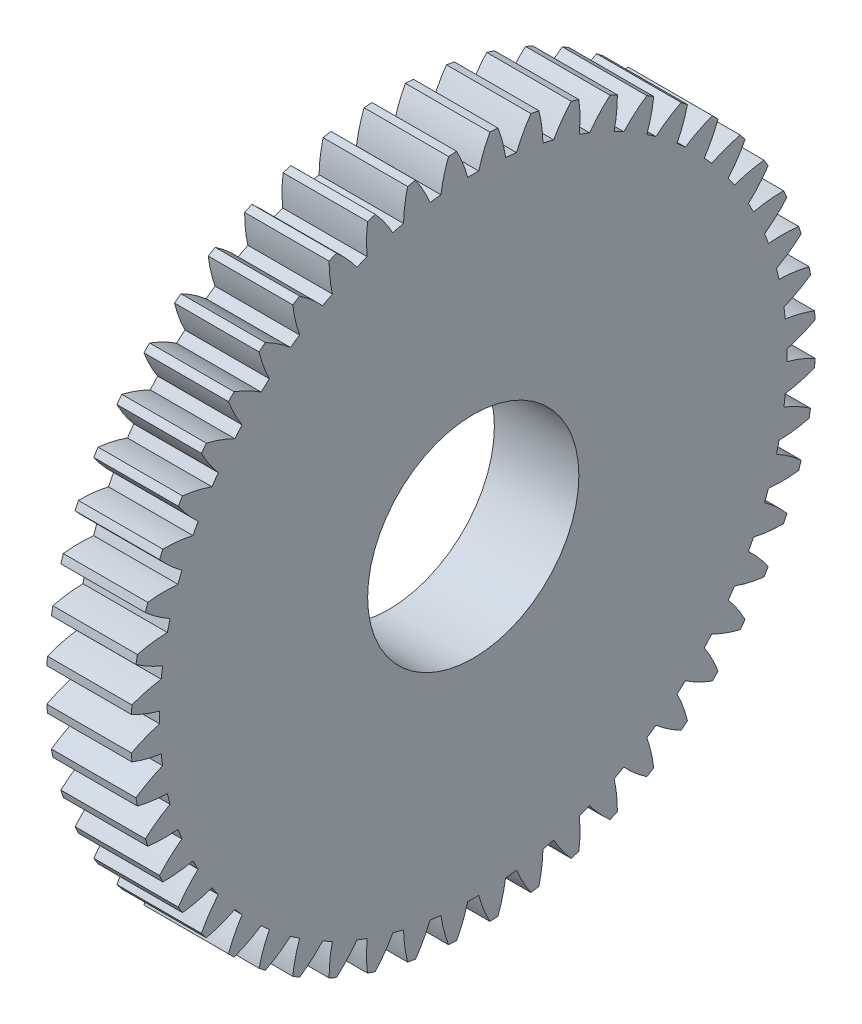
SolidWorks part; units mm, degrees
ref_plane "Plane1" through (0, 0, 0) normal (0, 0, 1) x (1, 0, 0)
ref_plane "Plane2" through (0, 0, 0) normal (0, 1, 0) x (1, 0, 0)
ref_plane "Plane3" through (0, 0, 0) normal (1, 0, 0) x (0, 0, -1)
sketch "HoldingSke" plane through (0, 0, 0) normal (0, 1, 0) x (1, 0, 0)
  line L0 (0, 0) -> (1.0261, -1.3134)
  line L1 (-15, 0) -> (100, 0) construction
  line L2 (0, 0) -> (-2.1039, 2.3779)
  line L3 (0, 0) -> (-11.863, 4.5341)
  line L4 (0, 0) -> (5.3169, 6.8053)
  line L5 (0, 0) -> (-46.8476, -17.4728)
  line L6 (0, 0) -> (-3.3159, -2.2372)
  line L7 (-2.1039, 2.3779) -> (8.6586, 51.2059)
  line L8 (-76.2, 54.61) -> (-74.4, 54.61)
  line L9 (-71.009, 38.7566) -> (-53.1078, 45.2721)
  line L10 (-76.2, 71.12) -> (104.1128, 71.12)
  line L11 (0, 0) -> (-4, 0)
  line L12 (-76.2, 101.6) -> (-76.177, 101.6)
  line L13 (24.9733, 27.94) -> (52.9518, 28.4284)
  line L14 (24.9733, 27.94) -> (24.9743, 27.94)
  line L15 (24.9733, 27.94) -> (100.4006, 29.5858)
  line L16 (-63.627, -0.6) -> (-12.827, -0.6)
  circle A0 centre (0, 0) radius 5
  circle A1 centre (0, 0) radius 14.849
  circle A2 centre (0, 0) radius 37.5
  circle A3 centre (0, 0) radius 5
  dimension "MHD" = 29.698
  dimension "Hub_dia" = 75
  dimension "Bore" = 10
  dimension "MBD" = 10
  dimension "Num_teeth" = 52
  dimension "Pitch" = 1.6667
  dimension "Overall_len" = 50
  dimension "Show_teeth" = 52
  dimension "Thickness" = 4
  dimension "OAL" = 50.0001
  dimension "T_dim" = 1.8
  dimension "Ap" = 20
  dimension "H" = 19.05
  dimension "Pitch_radius" = 180.3128
  dimension "Width" = 4
  dimension "Backlash" = 0.023
  dimension "Addendum_fac" = 1
  dimension "Dedendum_fac" = 1.25
  dimension "Clearance_fac" = 0.25
  dimension "Dedendum_add" = 0.001
  dimension "Module" = 0.6
sketch "BasProSke" plane through (0, 0, 0) normal (0, 1, 0) x (1, 0, 0)
  line L0 (-10, 0) -> (60, 0) construction
  line L1 (0, 0) -> (0, 16.2)
  line L2 (0, 0) -> (4, 0)
  line L3 (4, 0) -> (4, 16.2)
  line L4 (4, 16.2) -> (0, 16.2)
  dimension "Thickness" = 4
  dimension "Diameter" = 32.4
revolve "Base-Revolve" add sketch "BasProSke" angle 360 about L0
sketch "TooCutSke" plane through (0, 0, 0) normal (1, 0, 0) x (0, 0, -1)
  line L1 (0, 0) -> (0, 107) construction
  line L2 (0, 0) -> (-0.5114, 15.5916) construction
  line L3 (0, 0) -> (-1.8831, 31.1312) construction
  line L4 (-0.5114, 15.5916) -> (-0.9415, 15.5656) construction
  arc A0 (0.2618, 14.8467) -> (-0.2618, 14.8467) centre (0, 0) ccw
  arc A1 (0.801, 16.2056) -> (-0.801, 16.2056) centre (0, 0) ccw
  circle A2 centre (0, 0) radius 15.6 construction
  circle A3 centre (0, 0) radius 14.6592 construction
  arc A4 (-0.2618, 14.8467) -> (-0.801, 16.2056) centre (-6.2915, 13.2404) ccw
  arc A5 (0.801, 16.2056) -> (0.2618, 14.8467) centre (6.2915, 13.2404) ccw
  dimension "Root_dia" = 29.698
  dimension "Overcut_dia" = 32.4508
  dimension "Pitch_dia" = 31.2
  dimension "Base_dia" = 29.3184
  dimension "Flank_rad" = 6.24
  dimension "Half_ang" = 3.462
  dimension "Half_CT" = 0.4309
extrude "ToothCut" cut sketch "TooCutSke" along normal through all
fillet "Breaks" [suppressed] radius 0.012
fillet "RootFillets" [suppressed] radius 0.151
pattern_circular "TeethCuts" count 52 every 6.923 about axis through (-10, 0, 0) along (1, 0, 0) of "ToothCut", "RootFillets", "Breaks"
sketch "HubNeaOneSke" plane through (0, 0, 0) normal (-1, 0, 0) x (0, 0, 1)
  circle A0 centre (0, 0) radius 14.849
  dimension "Diameter" = 29.698
extrude "HubNearOne" [suppressed] add sketch "HubNeaOneSke" along normal blind 46.0001
sketch "HubNeaBotSke" plane through (0, 0, 0) normal (-1, 0, 0) x (0, 0, 1)
  circle A0 centre (0, 0) radius 14.849
  dimension "Diameter" = 29.698
extrude "HubNearBoth" [suppressed] add sketch "HubNeaBotSke" along normal blind 23
ref_plane "FarPln" through (4, 0, 0) normal (1, 0, 0) x (0, 0, -1)
sketch "HubFarSke" plane through (4, 0, 0) normal (1, 0, 0) x (0, 0, -1)
  circle A0 centre (0, 0) radius 14.849
  dimension "Diameter" = 29.698
extrude "HubFar" [suppressed] add sketch "HubFarSke" along normal blind 23
sketch "BorSke" plane through (0, 0, 0) normal (1, 0, 0) x (0, 0, -1)
  circle A0 centre (0, 0) radius 5
  dimension "Diameter" = 10
extrude "Bore" cut sketch "BorSke" along normal mid plane 100.0001
sketch "KeySke" plane through (0, 0, 0) normal (1, 0, 0) x (0, 0, -1)
  line L0 (-2, 0) -> (-2, 6.8)
  line L1 (-2, 6.8) -> (2, 6.8)
  line L2 (2, 6.8) -> (2, 0)
  line L3 (0, 0) -> (0, 34) construction
  line L4 (-2, 0) -> (2, 0)
  dimension "Width" = 4
  dimension "Offset" = 6.8
extrude "Keyway" [suppressed] cut sketch "KeySke" along normal mid plane 100.0001
pattern_circular "Keyway2" [suppressed] count 2 every 90 about axis through (-10, 0, 0) along (1, 0, 0)
equation "' \"Module@HoldingSke\" = 6.35"
equation "' \"Num_teeth@HoldingSke\" = 12"
equation "' \"Ap@HoldingSke\" =  20"
equation "' \"Ap@HoldingSke\" = 20"
equation "' \"Width@HoldingSke\" = 0.5 * 25.4"
equation "' \"Hub_dia@HoldingSke\"= 1 * 25.4"
equation "' \"Hub_dia@HoldingSke\" = 1 * 25.4"
equation "' \"Overall_len@HoldingSke\" = 1.0 * 25.4"
equation "' \"Bore@HoldingSke\" = 0.75 * 25.4"
equation "' \"T_dim@HoldingSke\" = 0.1 * 25.4"
equation "' \"Width@KeySke\" = 0.25 * 25.4"
equation "' \"Show_teeth@HoldingSke\" = 13"
equation "' \"Backlash@HoldingSke\" = 0.009 * 25.4"
equation "' \"Addendum_fac@HoldingSke\" = 1.0"
equation "' \"Dedendum_fac@HoldingSke\" = 1.25"
equation "' \"Dedendum_add@HoldingSke\" = 0.00005 * 25.4"
equation "' \"Clearance_fac@HoldingSke\" = 0.25"
equation "\"Pitch@HoldingSke\" = 1 / \"Module@HoldingSke\""
equation "\"Overcut_dia@TooCutSke\" = (\"Num_teeth@HoldingSke\" + 2 * \"Addendum_fac@HoldingSke\") / \"Pitch@HoldingSke\" + 0.002 * 25.4"
equation "\"Pitch_dia@TooCutSke\" = \"Num_teeth@HoldingSke\" / \"Pitch@HoldingSke\""
equation "\"Base_dia@TooCutSke\" = \"Num_teeth@HoldingSke\" / \"Pitch@HoldingSke\" * cos((\"Ap@HoldingSke\"  * 3.14159265 / 180))"
equation "\"Root_dia@TooCutSke\" = (\"Num_teeth@HoldingSke\" + 2) / \"Pitch@HoldingSke\" - 2 * (\"Addendum_fac@HoldingSke\" + \"Dedendum_fac@HoldingSke\") / \"Pitch@HoldingSke\" - \"Dedendum_add@HoldingSke\" * 2"
equation "\"Half_ang@TooCutSke\" = 180 / \"Num_teeth@HoldingSke\""
equation "\"Half_CT@TooCutSke\" = \"Num_teeth@HoldingSke\" / \"Pitch@HoldingSke\" * sin((3.14159265 / 2 / \"Num_teeth@HoldingSke\")) / 2 - 7 * \"Backlash@HoldingSke\" / 4"
equation "\"Flank_rad@TooCutSke\" = \"Num_teeth@HoldingSke\" / \"Pitch@HoldingSke\" / 5"
equation "\"Radius@RootFillets\" = \"Clearance_fac@HoldingSke\" / \"Pitch@HoldingSke\" + \"Dedendum_add@HoldingSke\""
equation "\"Break_rad@Breaks\" = 0.02 / \"Pitch@HoldingSke\""
equation "\"Thickness@HoldingSke\" = \"Width@HoldingSke\""
equation "\"OAL@HoldingSke\" = \"Thickness@HoldingSke\""
equation "\"MHD@HoldingSke\" = (\"Num_teeth@HoldingSke\" + 2) / \"Pitch@HoldingSke\" - 2 * (\"Addendum_fac@HoldingSke\" + \"Dedendum_fac@HoldingSke\")  / \"Pitch@HoldingSke\" - \"Dedendum_add@HoldingSke\" * 2"
equation "\"MBD@HoldingSke\" = (\"Num_teeth@HoldingSke\" + 2) / \"Pitch@HoldingSke\" - 2 * (\"Addendum_fac@HoldingSke\" + \"Dedendum_fac@HoldingSke\")  / \"Pitch@HoldingSke\" - \"Dedendum_add@HoldingSke\" * 2 - 0.002 * 25.4"
equation "\"MHD@HoldingSke\" = ((sgn( \"MHD@HoldingSke\" - \"Hub_dia@HoldingSke\" )-1)*( \"MHD@HoldingSke\" - \"Hub_dia@HoldingSke\" ))/-2+ \"Hub_dia@HoldingSke\""
equation "\"MBD@HoldingSke\" = ((sgn( \"MBD@HoldingSke\" - \"Bore@HoldingSke\" )-1)*( \"MBD@HoldingSke\" - \"Bore@HoldingSke\" ))/-2+ \"Bore@HoldingSke\""
equation "\"OAL@HoldingSke\" = ((sgn( \"OAL@HoldingSke\" - \"Overall_len@HoldingSke\" )+1)*( \"OAL@HoldingSke\" - \"Overall_len@HoldingSke\" ))/2 + \"Overall_len@HoldingSke\" + 0.000002 * 25.4"
equation "\"Num_teeth@TeethCuts\" = int( \"Show_teeth@HoldingSke\" ) + 1"
equation "\"Num_teeth@TeethCuts\" = ((sgn( \"Num_teeth@TeethCuts\" - \"Num_teeth@HoldingSke\" )-1)*( \"Num_teeth@TeethCuts\" - \"Num_teeth@HoldingSke\" ))/-2+ \"Num_teeth@HoldingSke\""
equation "\"Num_teeth@TeethCuts\" = ((sgn( \"Num_teeth@TeethCuts\" - 2.0)+1)*( \"Num_teeth@TeethCuts\" - 2.0))/2 +2.0"
equation "\"Angle@TeethCuts\" = 360.0 / \"Num_teeth@HoldingSke\""
equation "\"Diameter@BasProSke\" = (\"Num_teeth@HoldingSke\" + 2 * \"Addendum_fac@HoldingSke\") / \"Pitch@HoldingSke\""
equation "\"Thickness@BasProSke\"  = \"Thickness@HoldingSke\""
equation "' \"Fillet_rad@BasProSke\" =  \"Thickness@HoldingSke\" * 0.05"
equation "' \"Fillet_rad@BasProSke\" = \"Thickness@HoldingSke\" * 0.05"
equation "\"MHD@HoldingSke\" = ((sgn( \"MHD@HoldingSke\" - \"Root_dia@TooCutSke\" )-1)*( \"MHD@HoldingSke\" - \"Root_dia@TooCutSke\" ))/-2+ \"Root_dia@TooCutSke\""
equation "\"Diameter@HubNeaOneSke\" = \"MHD@HoldingSke\""
equation "\"Length@HubNearOne\" = \"OAL@HoldingSke\" - \"Thickness@BasProSke\""
equation "\"Diameter@HubNeaBotSke\" = \"MHD@HoldingSke\""
equation "\"Length@HubNearBoth\" = ( \"OAL@HoldingSke\" - \"Thickness@BasProSke\" ) / 2.0"
equation "\"Thickness@FarPln\" = \"Thickness@BasProSke\""
equation "\"Diameter@HubFarSke\" = \"MHD@HoldingSke\""
equation "\"Length@HubFar\" = ( \"OAL@HoldingSke\" - \"Thickness@BasProSke\" ) / 2.0"
equation "\"Diameter@BorSke\" = \"MBD@HoldingSke\""
equation "\"D1@Bore\" = \"OAL@HoldingSke\" * 2.0"
equation "\"D1@Keyway\" = \"OAL@HoldingSke\" * 2.0"
equation "\"Offset@KeySke\" = \"T_dim@HoldingSke\" + \"MBD@HoldingSke\" / 2.0"
